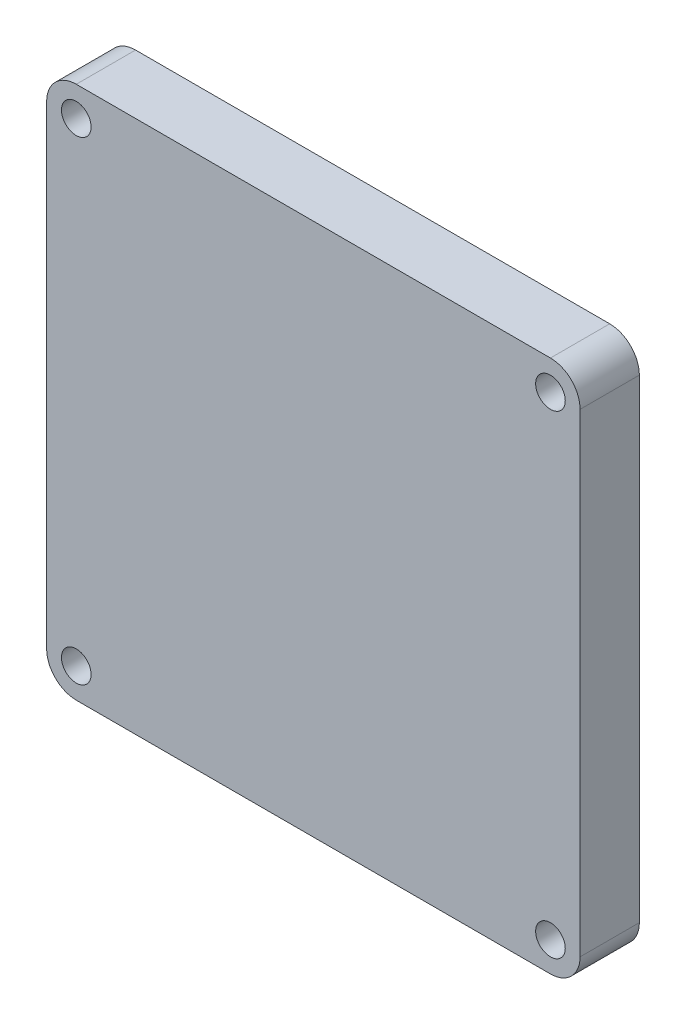
SolidWorks part; units mm, degrees
ref_plane "Front Plane" through (0, 0, 0) normal (0, 0, 1) x (1, 0, 0)
ref_plane "Top Plane" through (0, 0, 0) normal (0, 1, 0) x (1, 0, 0)
ref_plane "Right Plane" through (0, 0, 0) normal (1, 0, 0) x (0, 0, -1)
sketch "Sketch1" plane through (0, 0, 0) normal (0, 0, 1) x (1, 0, 0)
  line L1 (-45, 45) -> (45, 45)
  line L2 (-45, 45) -> (-45, -45)
  line L3 (-45, -45) -> (45, -45)
  line L4 (45, 45) -> (45, -45)
  line L5 (-45, 45) -> (45, -45) construction
  line L6 (-45, -45) -> (45, 45) construction
  point P0 (0, 0)
  dimension "D1" = 90
  dimension "D2" = 90
extrude "Boss-Extrude1" add sketch "Sketch1" along normal blind 10
fillet "Fillet1" radius 5 4 edges at (45, -45, 5) (-45, -45, 5) (-45, 45, 5) (45, 45, 5)
sketch "Sketch2" plane through (0, 0, 10) normal (0, 0, 1) x (1, 0, 0)
  circle A0 centre (-40, 40) radius 2.5
  circle A1 centre (40, 40) radius 2.5
  circle A2 centre (40, -40) radius 2.5
  circle A3 centre (-40, -40) radius 2.5
  dimension "D1" = 5
  dimension "D2" = 5
  dimension "D3" = 5
  dimension "D4" = 5
extrude "Cut-Extrude1" cut sketch "Sketch2" against normal blind 10
